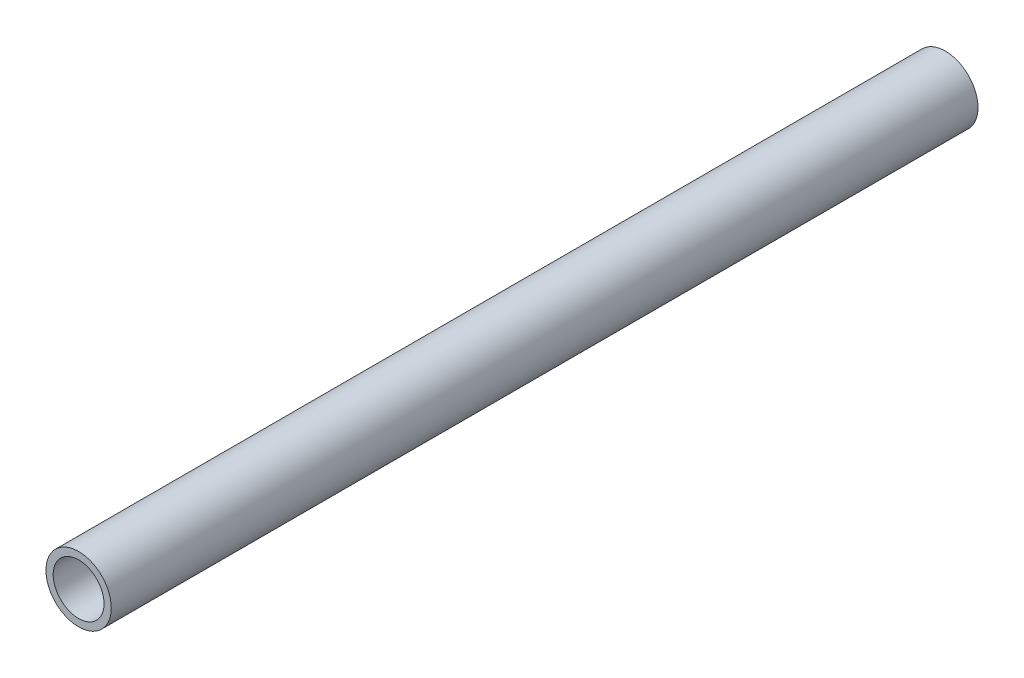
SolidWorks part; units mm, degrees
ref_plane "前视基准面" through (0, 0, 0) normal (0, 0, 1) x (1, 0, 0)
ref_plane "上视基准面" through (0, 0, 0) normal (0, 1, 0) x (1, 0, 0)
ref_plane "右视基准面" through (0, 0, 0) normal (1, 0, 0) x (0, 0, -1)
other "Configuration Table"
sketch "草图1" plane through (0, 0, 0) normal (0, 0, 1) x (1, 0, 0)
  circle A0 centre (0, 0) radius 7
  circle A1 centre (0, 0) radius 9
  dimension "D1" = 14
  dimension "D2" = 18
extrude "凸台-拉伸1" add sketch "草图1" along normal blind 238.73
